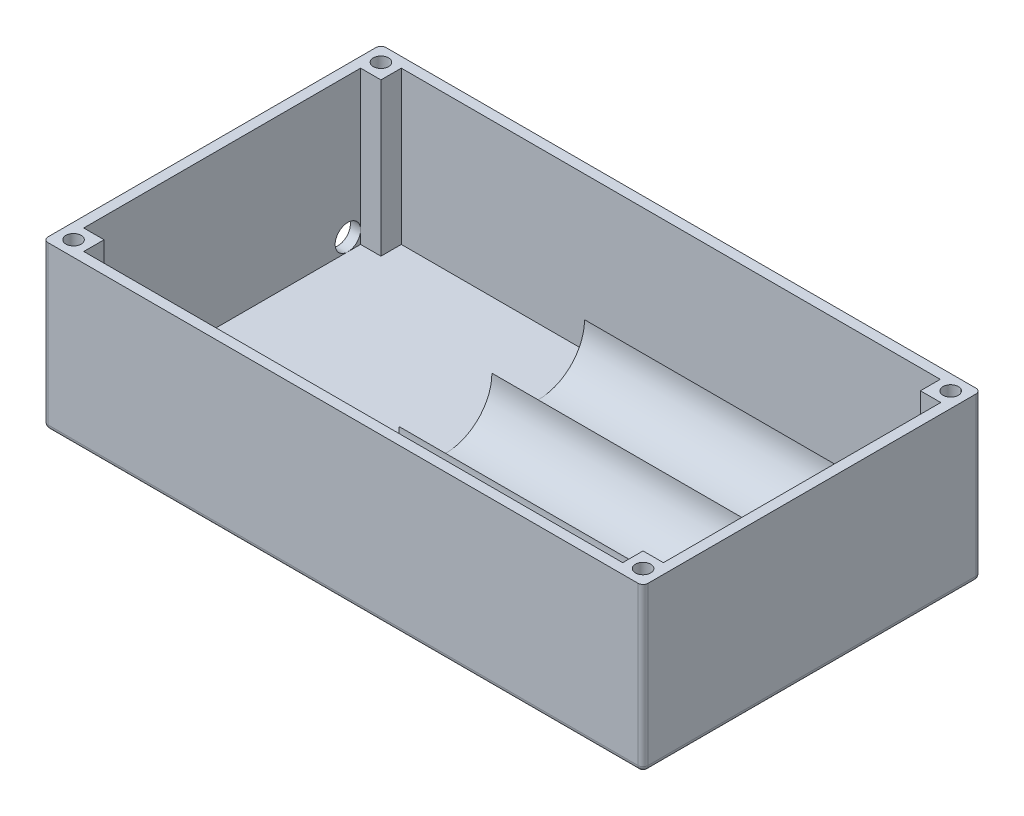
SolidWorks part; units mm, degrees
ref_plane "Front Plane" through (0, 0, 0) normal (0, 0, 1) x (1, 0, 0)
ref_plane "Top Plane" through (0, 0, 0) normal (0, 1, 0) x (1, 0, 0)
ref_plane "Right Plane" through (0, 0, 0) normal (1, 0, 0) x (0, 0, -1)
sketch "Sketch2" plane through (0, 0, 0) normal (0, 1, 0) x (1, 0, 0)
  line L1 (-60, 35) -> (60, 35)
  line L2 (-60, 35) -> (-60, -35)
  line L3 (-60, -35) -> (60, -35)
  line L4 (60, 35) -> (60, -35)
  line L5 (-60, 35) -> (60, -35) construction
  line L6 (-60, -35) -> (60, 35) construction
  point P0 (0, 0)
  dimension "D1" = 120
  dimension "D2" = 70
extrude "Boss-Extrude1" add sketch "Sketch2" along normal blind 30
shell "Shell1" thickness 2
sketch "Sketch3" plane through (-60, 0, 0) normal (1, 0, 0) x (0, 0, -1)
  line L0 (-35, 0) -> (35, 30) construction
  line L1 (-35, 30) -> (-35, 0) construction
  circle A0 centre (-28, 3) radius 2.5
  dimension "D1" = 7
  dimension "D2" = 5
extrude "Cut-Extrude1" cut sketch "Sketch3" against normal blind 30 and the other way through all
sketch "Sketch4" plane through (60, 0, 0) normal (-1, 0, 0) x (0, 0, 1)
  line L0 (-37, 30) -> (-37, -2) construction
  line L1 (-40.6627, 0) -> (41.472, 0) construction
  line L3 (-37, -2) -> (37, -2) construction
  line L4 (-31.1, 9.1) -> (-31.1, 0)
  line L5 (-31.1, 0) -> (23.5, 0)
  line L6 (23.5, 0) -> (23.5, 9.1)
  arc A0 (-31.1, 9.1) -> (-12.9, 9.1) centre (-22, 9.1) ccw
  arc A1 (-12.9, 9.1) -> (5.3, 9.1) centre (-3.8, 9.1) ccw
  arc A2 (5.3, 9.1) -> (23.5, 9.1) centre (14.4, 9.1) ccw
  line M4 (-35, 0) -> (35, 0)
  dimension "D1" = 18.2
  dimension "D2" = 18.2
  dimension "D3" = 18.2
  dimension "D4" = 18.2
  dimension "D5" = 18.2
  dimension "D6" = 15
  dimension "D7" = 2
extrude "Boss-Extrude2" add sketch "Sketch4" along normal blind 70 contours A1 A0 L5 | A2 A1 M4 | A2 L5 L6 | A0 L4 M4
sketch "Sketch5" plane through (0, 0, 0) normal (0, 1, 0) x (1, 0, 0)
  line L0 (-55.9, 35) -> (-55.9, -29.4) construction
  line L1 (60, 35) -> (-60, 35) construction
  line L2 (62, -29.4) -> (-79.3585, -29.4) construction
  line L3 (62, -37) -> (62, 37) construction
  line L4 (-10, -23.5) -> (60, -23.5) construction
  line L5 (-20, 35) -> (-20, -29.4) construction
  line L6 (60, 35) -> (-60, 35) construction
  line L7 (60, -35) -> (60, 35) construction
  line L8 (-50, 44.5462) -> (-50, -29.4) construction
  line L11 (62, 37) -> (-62, 37) construction
  line L12 (-10, 31.1) -> (60, 31.1) construction
  line L13 (-55.9, 39.544) -> (-55.9, -29.4)
  line L14 (-55.9, -41.3016) -> (-67.0587, -41.3016)
  line L15 (-67.0587, -41.3016) -> (-67.0587, 39.544)
  line L16 (-67.0587, 39.544) -> (-55.9, 39.544)
  line L17 (62, -29.4) -> (-55.9, -29.4)
  line L18 (62, -29.4) -> (62, -41.3016)
  line L19 (62, -41.3016) -> (-55.9, -41.3016)
  line L20 (-50, -41.3016) -> (-50, -46.7093) construction
  line L21 (-55.9, -41.3016) -> (-55.9, -49.0076) construction
  dimension "D1" = 5.9
  dimension "D2" = 117.9
  dimension "D3" = 80
  dimension "D4" = 30
  dimension "D5" = 2
  dimension "D6" = 3.9
extrude "Cut-Extrude2" cut sketch "Sketch5" against normal through all both and the other way through all
sketch "Sketch6" plane through (0, 0, 0) normal (0, 1, 0) x (1, 0, 0)
  line L0 (-55.9, 35) -> (-55.9, -29.4)
  line L1 (-55.9, -29.4) -> (62, -29.4)
  line L2 (62, -29.4) -> (62, -27.4)
  line L4 (62, -27.4) -> (-53.9, -27.4)
  line L5 (-53.9, -27.4) -> (-53.9, 35)
  line L6 (60, 35) -> (-55.9, 35) construction
  line L7 (-55.9, 35) -> (-53.9, 35)
  point P4 (0, 0)
  point P14 (0, 0)
  dimension "D1" = 2
  dimension "D2" = 2
extrude "Boss-Extrude3" add sketch "Sketch6" along normal up to surface (30 mm away)
sketch "Sketch7" plane through (62, 0, 0) normal (1, 0, 0) x (0, 0, -1)
  line L1 (-28.4153, 6.4348) -> (-24.5784, 6.4348)
  line L2 (-28.4153, 6.4348) -> (-28.4153, 0)
  line L3 (-28.4153, 0) -> (-24.5784, 0)
  line L4 (-24.5784, 6.4348) -> (-24.5784, 0)
extrude "Boss-Extrude4" add sketch "Sketch7" against normal up to surface (2 mm away) up to face at (60, 6.2583, 1.2417)
sketch "Sketch8" plane through (-53.9, 0, 0) normal (1, 0, 0) x (0, 0, -1)
  line L0 (31, 11.0115) -> (31, -5.4979) construction
  line L1 (21.6549, 0) -> (40.267, 0) construction
  line L2 (37, 30) -> (37, -2) construction
  circle A0 centre (28.5, 2.5) radius 2.5
  dimension "D1" = 5
  dimension "D2" = 6
extrude "Cut-Extrude5" cut sketch "Sketch8" against normal blind 5
sketch "Sketch10" plane through (0, 30, 0) normal (0, 1, 0) x (1, 0, 0)
  line L0 (-10, 31.1) -> (60, 31.1) construction
  line L1 (-55.9, 37) -> (-49.9, 37)
  line L2 (-55.9, 37) -> (-55.9, 31)
  line L3 (-55.9, 31) -> (-49.9, 31)
  line L4 (-49.9, 37) -> (-49.9, 31)
  line L5 (-55.9, -29.4) -> (-49.9, -29.4)
  line L6 (-55.9, -29.4) -> (-55.9, -23.4)
  line L7 (-55.9, -23.4) -> (-49.9, -23.4)
  line L8 (-49.9, -29.4) -> (-49.9, -23.4)
  line L9 (62, 37) -> (56, 37)
  line L10 (62, 37) -> (62, 31.1)
  line L11 (62, 31.1) -> (56, 31.1)
  line L12 (56, 37) -> (56, 31.1)
  line L14 (62, -29.4) -> (56, -29.4)
  line L15 (62, -29.4) -> (62, -23.4)
  line L16 (62, -23.4) -> (56, -23.4)
  line L17 (56, -29.4) -> (56, -23.4)
  dimension "D1" = 6
  dimension "D2" = 6
  dimension "D3" = 6
  dimension "D4" = 6
  dimension "D5" = 6
  dimension "D6" = 6
  dimension "D7" = 6
extrude "Boss-Extrude5" add sketch "Sketch10" against normal up to surface (30 mm away)
sketch "Sketch11" plane through (-55.9, 0, 0) normal (-1, 0, 0) x (0, 0, 1)
  line L1 (-33.4091, 7.0467) -> (-27.328, 7.0467)
  line L2 (-33.4091, 7.0467) -> (-33.4091, 0)
  line L3 (-33.4091, 0) -> (-27.328, 0)
  line L4 (-27.328, 7.0467) -> (-27.328, 0)
sketch "Sketch12" plane through (0, 30, 0) normal (0, 1, 0) x (1, 0, 0)
  line L0 (-49.9, 31) -> (-55.9, 31) construction
  line L1 (-55.9, 37) -> (-55.9, 31) construction
  line L2 (56, 31.1) -> (62, 31.1) construction
  line L3 (62, -29.4) -> (62, 37) construction
  line L4 (62, 31.1) -> (62, 37) construction
  line L5 (56, -23.4) -> (62, -23.4) construction
  line L6 (62, -23.4) -> (62, -29.4) construction
  line L7 (-49.9, -23.4) -> (-55.9, -23.4) construction
  line L8 (-55.9, -29.4) -> (-55.9, 37) construction
  line L9 (-55.9, -23.4) -> (-55.9, -29.4) construction
  circle A0 centre (-52.9, 34) radius 1.5
  circle A1 centre (59, 34.05) radius 1.5
  circle A2 centre (59, -26.4) radius 1.5
  circle A3 centre (-52.9, -26.4) radius 1.5
  dimension "D1" = 3
  dimension "D2" = 3
  dimension "D3" = 3
  dimension "D4" = 3
extrude "Cut-Extrude6" cut sketch "Sketch12" against normal blind 15
fillet "Fillet2" radius 1 8 edges at (-55.9, -2, -3.8) (62, -2, -3.8) (3.05, -2, -37) (3.05, -2, 29.4) (-55.9, 14, -37) (-55.9, 14, 29.4) (62, 14, 29.4) (62, 14, -37)
